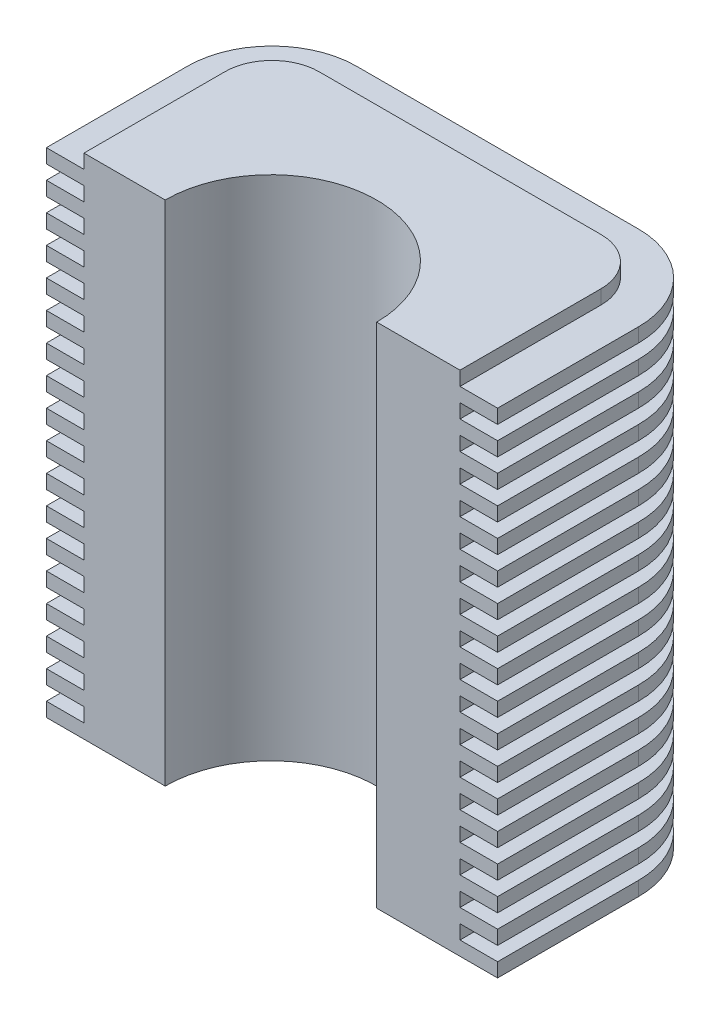
SolidWorks part; units mm, degrees
ref_plane "Płaszczyzna przednia" through (0, 0, 0) normal (0, 0, 1) x (1, 0, 0)
ref_plane "Płaszczyzna górna" through (0, 0, 0) normal (0, 1, 0) x (1, 0, 0)
ref_plane "Płaszczyzna prawa" through (0, 0, 0) normal (1, 0, 0) x (0, 0, -1)
sketch "Szkic1" plane through (0, 0, 0) normal (0, 1, 0) x (1, 0, 0)
  line L0 (-22.5, 0) -> (-39.7802, 0)
  line L1 (-39.7802, 0) -> (-39.7802, 40)
  line L2 (-39.7802, 40) -> (40.2198, 40)
  line L3 (40.2198, 40) -> (40.2198, 0)
  line L4 (40.2198, 0) -> (22.5, 0)
  arc A0 (22.5, 0) -> (-22.5, 0) centre (0, 0) ccw
  dimension "D1" = 45
  dimension "D2" = 80
  dimension "D3" = 40
extrude "Dodanie-wyciągnięcie1" add sketch "Szkic1" along normal blind 108
fillet "Zaokrąglenie1" radius 10 1 edges at (40.2198, 54, -40)
fillet "Zaokrąglenie2" radius 10 1 edges at (-39.7802, 54, -40)
sketch "Szkic4" plane through (0, 0, 0) normal (0, 1, 0) x (1, 0, 0)
  line L0 (40.2198, 0) -> (40.2198, 30) construction
  line L1 (30.2198, 40) -> (-29.7802, 40) construction
  line L2 (-39.7802, 30) -> (-39.7802, 0) construction
  line L3 (40.2198, 0) -> (40.2198, 30)
  line L4 (30.2198, 40) -> (-29.7802, 40)
  line L5 (-39.7802, 30) -> (-39.7802, 0)
  line L6 (48.2198, 0) -> (48.2198, 30)
  line L7 (30.2198, 48) -> (-29.7802, 48)
  line L8 (-47.7802, 30) -> (-47.7802, 0)
  line L9 (-47.7802, 0) -> (-39.7802, 0)
  line L10 (40.2198, 0) -> (48.2198, 0)
  arc A0 (40.2198, 30) -> (30.2198, 40) centre (30.2198, 30) ccw construction
  arc A1 (-29.7802, 40) -> (-39.7802, 30) centre (-29.7802, 30) ccw construction
  arc A2 (40.2198, 30) -> (30.2198, 40) centre (30.2198, 30) ccw
  arc A3 (-29.7802, 40) -> (-39.7802, 30) centre (-29.7802, 30) ccw
  arc A4 (48.2198, 30) -> (30.2198, 48) centre (30.2198, 30) ccw
  arc A5 (-29.7802, 48) -> (-47.7802, 30) centre (-29.7802, 30) ccw
  dimension "D1" = 8
extrude "Dodanie-wyciągnięcie4" add sketch "Szkic4" along normal blind 3
pattern_linear "Szyk liniowy1" count 18 spacing 6 along (0, 1, 0) of "Dodanie-wyciągnięcie4"
